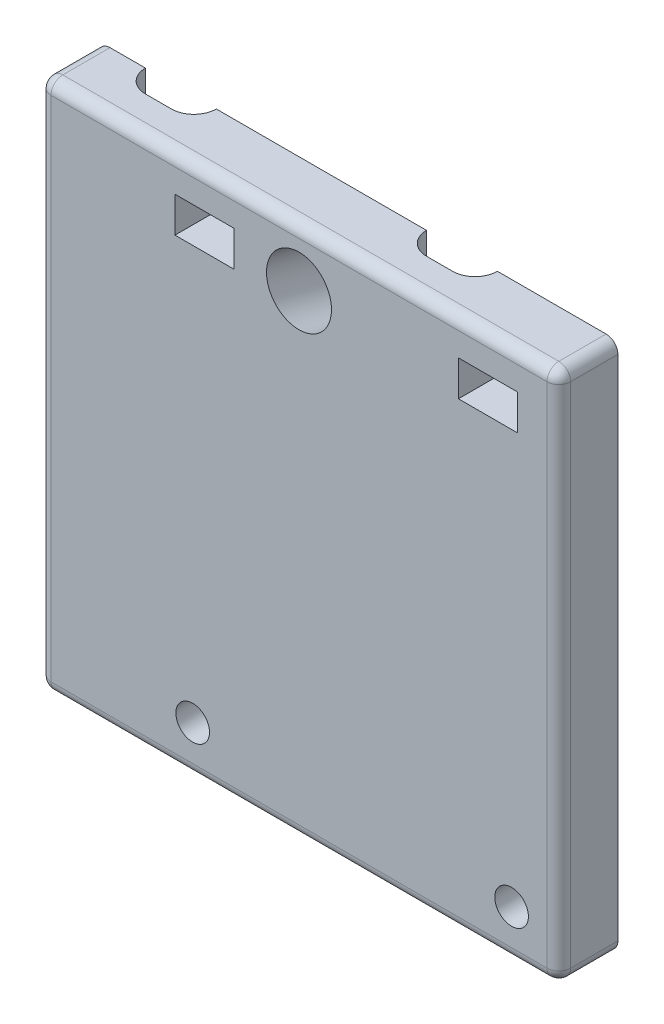
SolidWorks part; units mm, degrees
ref_plane "Front Plane" through (0, 0, 0) normal (0, 0, 1) x (1, 0, 0)
ref_plane "Top Plane" through (0, 0, 0) normal (0, 1, 0) x (1, 0, 0)
ref_plane "Right Plane" through (0, 0, 0) normal (1, 0, 0) x (0, 0, -1)
sketch "Sketch1" plane through (0, 0, 0) normal (0, 0, 1) x (1, 0, 0)
  line L1 (-22, 22.5) -> (22, 22.5)
  line L2 (-22, 22.5) -> (-22, -22.5)
  line L3 (-22, -22.5) -> (22, -22.5)
  line L4 (22, 22.5) -> (22, -22.5)
  line L5 (-22, 22.5) -> (22, -22.5) construction
  line L6 (-22, -22.5) -> (22, 22.5) construction
  point P0 (0, 0)
  dimension "D1" = 44
  dimension "D2" = 45
extrude "Base" add sketch "Sketch1" along normal blind 5
sketch "Sketch2" plane through (0, 22.5, 0) normal (0, 1, 0) x (1, 0, 0)
  line L0 (22, 0) -> (-22, 0) construction
  line L1 (-18, 0) -> (-12, 0)
  line L2 (0, 0) -> (0, -5) construction
  line L3 (22, -5) -> (-22, -5) construction
  line L5 (-16.1, -1.9) -> (-13.9, -1.9)
  line L6 (-18, 0) -> (-18, -5) construction
  line L7 (-3.1, 0) -> (-3.1, -5) construction
  line L8 (9.9, -1.9) -> (7.7, -1.9)
  line L9 (11.8, 0) -> (5.8, 0)
  arc A2 (-16.1, -1.9) -> (-18, 0) centre (-16.1, 0) cw
  arc A3 (-12, 0) -> (-13.9, -1.9) centre (-13.9, 0) cw
  arc A4 (9.9, -1.9) -> (11.8, 0) centre (9.9, 0) ccw
  arc A5 (5.8, 0) -> (7.7, -1.9) centre (7.7, 0) ccw
  point P0 (-15, 0)
  point P15 (-15, -1.9)
  dimension "D1" = 15
  dimension "D2" = 6
  dimension "D3" = 1.9
  dimension "D4" = 11.9
extrude "Wire Grooves" cut sketch "Sketch2" against normal through all
sketch "Sketch4" plane through (0, 0, 0) normal (0, 0, -1) x (-1, 0, 0)
  line L0 (0, 22.5) -> (0, -22.5) construction
  line L3 (-22, 16.5291) -> (22, 16.5291) construction
  line L4 (-22, -22.5) -> (-22, 22.5) construction
  line L5 (22, 22.5) -> (22, -22.5) construction
  line L6 (-22, 22.5) -> (-11.8, 22.5) construction
  line L7 (12, -22.5) -> (-5.8, -22.5) construction
  point P2 (0, 0)
  point P3 (0, 0)
  point P14 (0, 0)
  point P15 (0, 0)
  dimension "D1" = 5.9709
ref_plane "Screw Insertion Hole Reference" through (0, 1.1072, 4.1323) normal (0, -0.2588, -0.9659) x (-1, 0, 0)
sketch "Sketch3" plane through (0, 0.5961, 4.2692) normal (0, -0.2588, -0.9659) x (-1, 0, 0)
  line L0 (0, 0.5291) -> (0, 22.2625) construction
  line L2 (-22, 22.2625) -> (-11.8, 22.2625) construction
  circle A0 centre (0, 16.2916) radius 2.75
  point P7 (0, 0)
  point P10 (0, 0)
  point P11 (0, 0)
  dimension "D1" = 5.5
  dimension "D2" = 5.9709
extrude "Screw Insertion Hole" cut sketch "Sketch3" against normal through all both and the other way through all
sketch "Sketch5" plane through (0, 0, 0) normal (0, 0, -1) x (-1, 0, 0)
  line L1 (-22, 22.5) -> (-11.8, 22.5) construction
  line L3 (0, 22.5) -> (0, -22.5) construction
  line L7 (-18.5, 19.5) -> (-13.5, 19.5)
  line L8 (-18.5, 19.5) -> (-18.5, 16.5)
  line L9 (-18.5, 16.5) -> (-13.5, 16.5)
  line L10 (-13.5, 19.5) -> (-13.5, 16.5)
  line L11 (-18.5, 19.5) -> (-13.5, 16.5) construction
  line L12 (-18.5, 16.5) -> (-13.5, 19.5) construction
  line L16 (-22, 22.5) -> (-11.8, 22.5) construction
  line L20 (12, -22.5) -> (-5.8, -22.5) construction
  line L21 (-4, 22.5) -> (-4, -22.5) construction
  line L22 (-5.8, 22.5) -> (12, 22.5) construction
  line L23 (12, -22.5) -> (-5.8, -22.5) construction
  line L24 (10.5, 16.5) -> (5.5, 16.5)
  line L25 (5.5, 19.5) -> (5.5, 16.5)
  line L26 (10.5, 19.5) -> (5.5, 19.5)
  line L27 (10.5, 19.5) -> (10.5, 16.5)
  point P12 (-16, 18)
  dimension "D1" = 5
  dimension "D2" = 3
  dimension "D3" = 3
  dimension "D4" = 16
  dimension "D5" = 4
extrude "Zip Tie Slots" cut sketch "Sketch5" against normal through all
sketch "Sketch6" plane through (0, 0, 0) normal (0, 0, -1) x (-1, 0, 0)
  line L1 (-22, -22.5) -> (-22, 22.5) construction
  line L2 (12, -22.5) -> (-5.8, -22.5) construction
  line L4 (-4.5, 22.5) -> (-4.5, -22.5) construction
  line L6 (-22, 22.5) -> (-11.8, 22.5) construction
  circle A0 centre (-18, -18.5) radius 1.425
  circle A2 centre (9, -18.5) radius 1.425
  dimension "D1" = 2.85
  dimension "D2" = 4
  dimension "D3" = 4
  dimension "D4" = 4.5
extrude "Mount Clamping Holes" cut sketch "Sketch6" against normal through all
fillet "Edge Fillets" radius 1 8 edges at (-22, 0, 5) (22, 0, 5) (0, -22.5, 5) (0, 22.5, 5) (22, 22.5, 2.5) (22, -22.5, 2.5) (-22, -22.5, 2.5) (-22, 22.5, 2.5)
